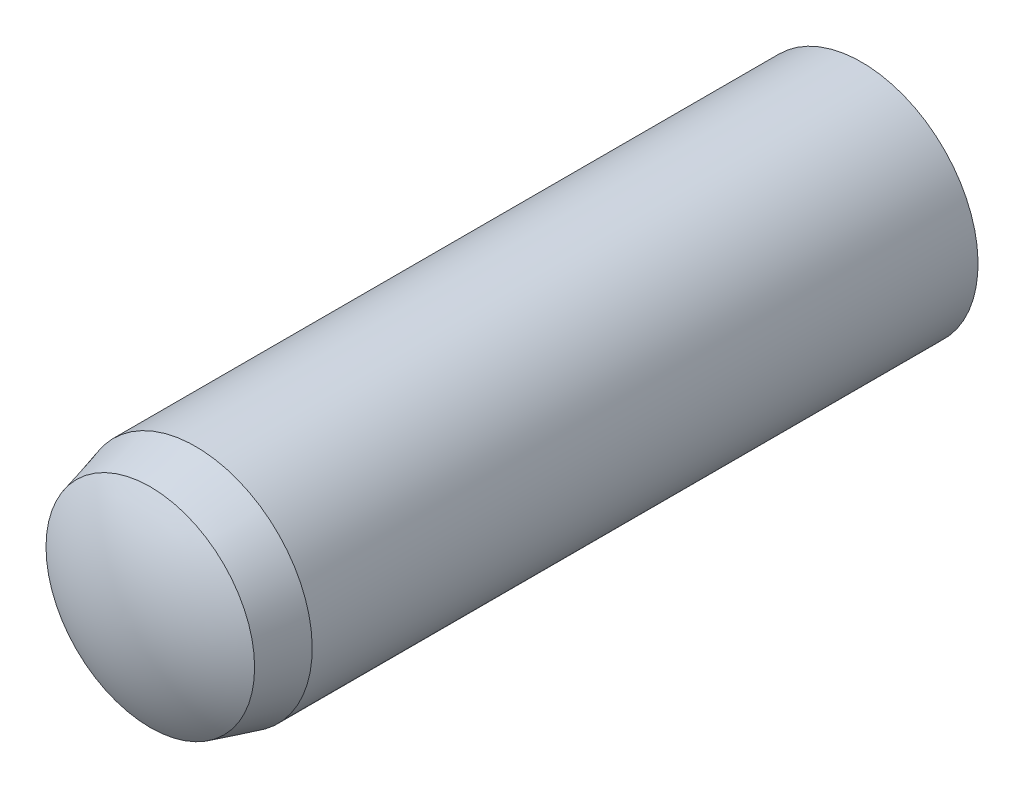
SolidWorks part; units mm, degrees
ref_plane "Front Plane" through (0, 0, 0) normal (0, 0, 1) x (1, 0, 0)
ref_plane "Top Plane" through (0, 0, 0) normal (0, 1, 0) x (1, 0, 0)
ref_plane "Right Plane" through (0, 0, 0) normal (1, 0, 0) x (0, 0, -1)
sketch "Sketch1" plane through (0, 0, 0) normal (0, 0, 1) x (1, 0, 0)
  circle A0 centre (0, 0) radius 1.5
  point P3 (0, 1.5)
  dimension "Diameter" = 3
sketch "Sketch2" plane through (0, 0, 0) normal (1, 0, 0) x (0, 0, -1)
  line L0 (-5, 0) -> (5, 0) construction
  line L1 (-5, 0) -> (-5, 1.5) construction
  line L2 (-5, 1.5) -> (5, 1.5)
  line L3 (5, 1.5) -> (5, 0) construction
  line L4 (-4.61, 1.3432) -> (-4.025, 1.5)
  arc A0 (-5, 0) -> (-4.61, 1.3432) centre (-2.4918, 0) cw
  arc A1 (5, 0) -> (4.55, 1.5) centre (2.275, 0) ccw
  point P2 (0, 0)
  point P11 (-2, 0)
  point P13 (2, 0)
  dimension "Length" = 10
  dimension "D1" = 15
  dimension "D2" = 0.45
  dimension "D3" = 0.975
  dimension "D4" = 0.585
  dimension "D5" = 3
  dimension "D6" = 3
sketch "Sketch3" plane through (0, 0, 0) normal (1, 0, 0) x (0, 0, -1)
  line L0 (-5, 0) -> (5, 0) construction
  line L1 (-4.61, 1.3432) -> (-4.025, 1.5) construction
  line L2 (-5, 0) -> (5, 0)
  line L3 (-4.61, 1.3432) -> (-4.025, 1.5)
  line L4 (-4.025, 1.5) -> (4.55, 1.5)
  arc A0 (5, 0) -> (4.55, 1.5) centre (2.275, 0) ccw construction
  arc A1 (-4.61, 1.3432) -> (-5, 0) centre (-2.4918, 0) ccw construction
  arc A2 (5, 0) -> (4.55, 1.5) centre (2.275, 0) ccw
  arc A3 (-4.61, 1.3432) -> (-5, 0) centre (-2.4918, 0) ccw
revolve "Revolve1" add sketch "Sketch3" angle 360 about L2
equation "\"D2@Sketch2\" = \"Diameter@Sketch1\" * .15"
equation "\"D3@Sketch2\" = \"Diameter@Sketch1\" * .325"
equation "\"D4@Sketch2\" = \"D3@Sketch2\" * .6"
equation "\"D5@Sketch2\"=\"Diameter@Sketch1\""
equation "\"D6@Sketch2\"=\"D5@sketch2\""
